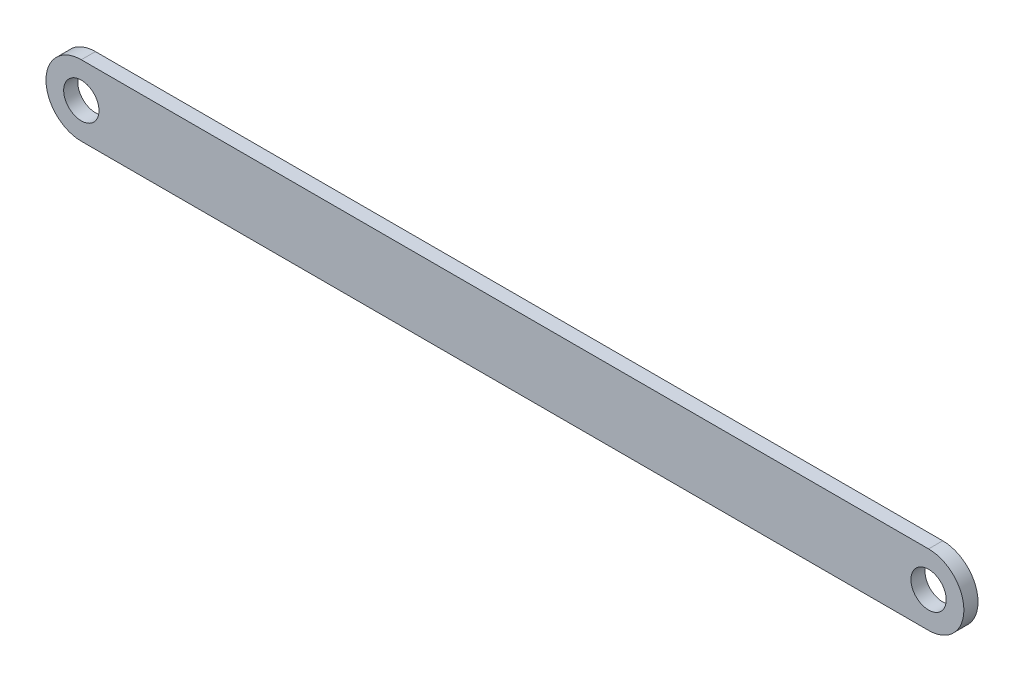
SolidWorks part; units mm, degrees
ref_plane "Front Plane" through (0, 0, 0) normal (0, 0, 1) x (1, 0, 0)
ref_plane "Top Plane" through (0, 0, 0) normal (0, 1, 0) x (1, 0, 0)
ref_plane "Right Plane" through (0, 0, 0) normal (1, 0, 0) x (0, 0, -1)
sketch "Sketch1" plane through (0, 0, 0) normal (0, 0, 1) x (1, 0, 0)
  line L0 (-34.4915, 0) -> (85.5085, 0) construction
  line L1 (-34.4915, 5) -> (85.5085, 5)
  line L2 (-34.4915, -5) -> (85.5085, -5)
  arc A0 (-34.4915, 5) -> (-34.4915, -5) centre (-34.4915, 0) ccw
  arc A1 (85.5085, -5) -> (85.5085, 5) centre (85.5085, 0) ccw
  circle A2 centre (-34.4915, 0) radius 2.5
  circle A3 centre (85.5085, 0) radius 2.5
  point P3 (25.5085, 0)
  dimension "D1" = 10
  dimension "D2" = 120
extrude "Boss-Extrude1" add sketch "Sketch1" along normal blind 2
